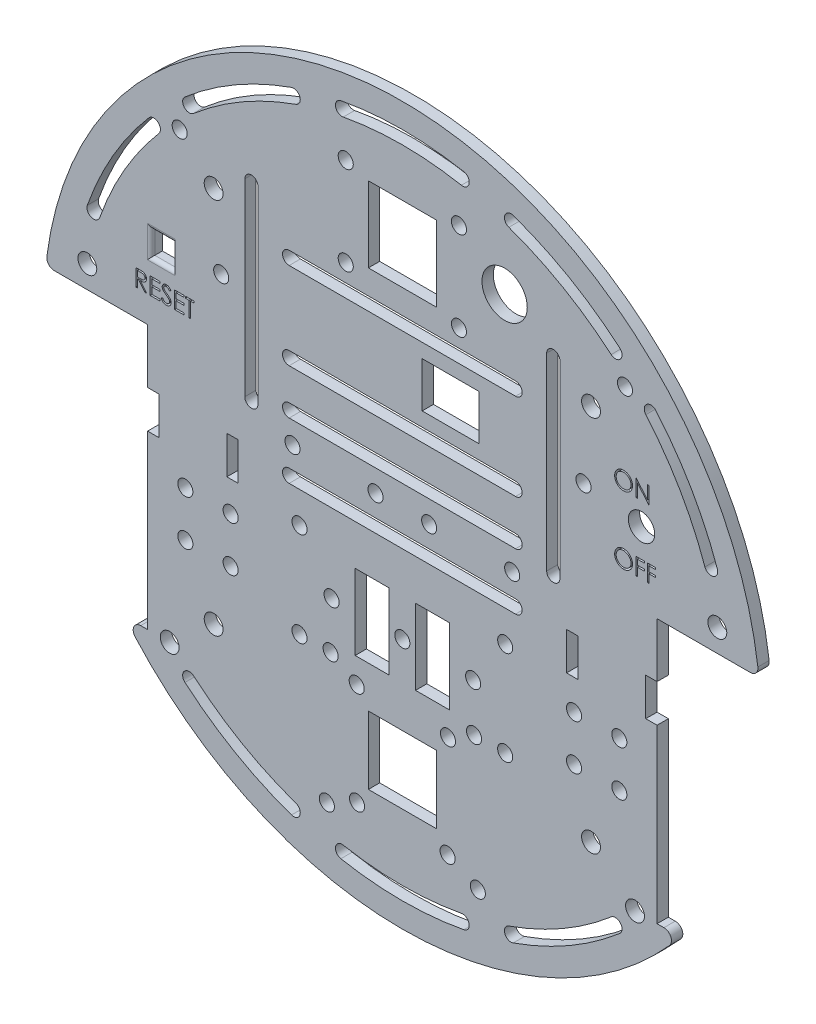
SolidWorks part; units mm, degrees
ref_plane "Alzado" through (0, 0, 0) normal (0, 0, 1) x (1, 0, 0)
ref_plane "Planta" through (0, 0, 0) normal (0, 1, 0) x (1, 0, 0)
ref_plane "Vista lateral" through (0, 0, 0) normal (1, 0, 0) x (0, 0, -1)
sketch "Croquis1" plane through (0, 0, 0) normal (0, 0, 1) x (1, 0, 0)
  line L0 (-73.6546, -60) -> (-67.5, -60)
  line L1 (-67.5, -60) -> (-67.5, -14.4456)
  line L2 (-67.5, 10) -> (-94.4722, 10)
  line L3 (0, 0) -> (0, 95) construction
  line L4 (67.5, 10) -> (94.4722, 10)
  line L5 (67.5, -60) -> (67.5, -14.4456)
  line L6 (73.6546, -60) -> (67.5, -60)
  line L7 (0, 0) -> (0, -95) construction
  line L8 (-66.5, -28.4456) -> (0, -28.4456) construction
  line L9 (12.5, -18.4456) -> (3.5, -18.4456)
  line L10 (-12.5, -38.4456) -> (-3.5, -38.4456)
  line L11 (-12.5, -38.4456) -> (-12.5, -18.4456)
  line L12 (-12.5, -18.4456) -> (-3.5, -18.4456)
  line L13 (-3.5, -38.4456) -> (-3.5, -18.4456)
  line L14 (-12.5, -38.4456) -> (-3.5, -18.4456) construction
  line L15 (-12.5, -18.4456) -> (-3.5, -38.4456) construction
  line L16 (3.5, -38.4456) -> (3.5, -18.4456)
  line L17 (12.5, -38.4456) -> (3.5, -38.4456)
  line L18 (12.5, -38.4456) -> (12.5, -18.4456)
  line L19 (-30, 9.0544) -> (30, 9.0544) construction
  line L22 (-30, 21.0544) -> (30, 21.0544) construction
  line L25 (0, 0) -> (-47.5, -82.2724) construction
  line L26 (-9, 52.25) -> (9, 52.25)
  line L27 (0, 0) -> (-82.2724, -47.5) construction
  line L28 (0, 0) -> (-95, 0) construction
  line L29 (0, 0) -> (-82.2724, 47.5) construction
  line L30 (0, 0) -> (-47.5, 82.2724) construction
  line L31 (0, 0) -> (0, 95) construction
  line L32 (0, 0) -> (47.5, 82.2724) construction
  line L33 (0, 0) -> (82.2724, 47.5) construction
  line L34 (0, 0) -> (95, 0) construction
  line L35 (0, 0) -> (82.2724, -47.5) construction
  line L36 (0, 0) -> (47.5, -82.2724) construction
  line L41 (-30, -5.9456) -> (30, -5.9456) construction
  line L42 (-30, -7.6956) -> (30, -7.6956)
  line L43 (-30, -4.1956) -> (30, -4.1956)
  line L44 (-9, -67.4313) -> (9, -67.4313)
  line L58 (-9, 52.25) -> (-9, 72.25)
  line L59 (-9, 72.25) -> (9, 72.25)
  line L61 (-40, 6.316) -> (-40, 56.316) construction
  line L62 (-41.75, 6.316) -> (-41.75, 56.316)
  line L63 (-38.25, 6.316) -> (-38.25, 56.316)
  line L64 (40, 6.316) -> (40, 56.316) construction
  line L65 (41.75, 6.316) -> (41.75, 56.316)
  line L66 (38.25, 6.316) -> (38.25, 56.316)
  line L67 (-30, 10.8044) -> (30, 10.8044)
  line L68 (-30, 7.3044) -> (30, 7.3044)
  line L71 (-30, 44.0544) -> (30, 44.0544) construction
  line L72 (-30, 45.8044) -> (30, 45.8044)
  line L73 (-30, 42.3044) -> (30, 42.3044)
  line L74 (-67.5, -4.4456) -> (-64.5, -4.4456)
  line L75 (-46.5, -4.4456) -> (-43.5, -4.4456)
  line L76 (-46.5, -4.4456) -> (-46.5, -14.4456)
  line L77 (-46.5, -14.4456) -> (-43.5, -14.4456)
  line L78 (-43.5, -4.4456) -> (-43.5, -14.4456)
  line L79 (-46.5, -4.4456) -> (-43.5, -14.4456) construction
  line L80 (-46.5, -14.4456) -> (-43.5, -4.4456) construction
  line L81 (-64.5, -4.4456) -> (-64.5, -14.4456)
  line L82 (-64.5, -14.4456) -> (-67.5, -14.4456)
  line L83 (46.5, -14.4456) -> (43.5, -4.4456) construction
  line L84 (46.5, -4.4456) -> (43.5, -14.4456) construction
  line L85 (46.5, -14.4456) -> (43.5, -14.4456)
  line L86 (43.5, -4.4456) -> (43.5, -14.4456)
  line L87 (46.5, -4.4456) -> (46.5, -14.4456)
  line L88 (46.5, -4.4456) -> (43.5, -4.4456)
  line L89 (64.5, -14.4456) -> (67.5, -14.4456)
  line L90 (64.5, -4.4456) -> (64.5, -14.4456)
  line L91 (67.5, -4.4456) -> (64.5, -4.4456)
  line L92 (-67.5, -4.4456) -> (-67.5, 10)
  line L93 (67.5, -4.4456) -> (67.5, 10)
  line L94 (-9, -67.4313) -> (-9, -49.4313)
  line L95 (-9, -49.4313) -> (9, -49.4313)
  line L96 (9, -67.4313) -> (9, -49.4313)
  line L97 (-9, -67.4313) -> (9, -49.4313) construction
  line L98 (-9, -49.4313) -> (9, -67.4313) construction
  line L99 (9, 52.25) -> (9, 72.25)
  line L100 (-9, 52.25) -> (9, 72.25) construction
  line L101 (-9, 72.25) -> (9, 52.25) construction
  line L102 (-30, 22.8044) -> (30, 22.8044)
  line L103 (-30, 19.3044) -> (30, 19.3044)
  line L105 (5.25, 26.5544) -> (20.25, 26.5544)
  line L106 (5.25, 26.5544) -> (5.25, 38.5544)
  line L107 (5.25, 38.5544) -> (20.25, 38.5544)
  line L108 (20.25, 26.5544) -> (20.25, 38.5544)
  line L109 (5.25, 26.5544) -> (20.25, 38.5544) construction
  line L110 (5.25, 38.5544) -> (20.25, 26.5544) construction
  line L111 (-66.5827, 25.8443) -> (-60.1827, 25.8443)
  line L112 (-66.5827, 25.8443) -> (-66.5827, 32.2443)
  line L113 (-66.5827, 32.2443) -> (-60.1827, 32.2443)
  line L114 (-60.1827, 25.8443) -> (-60.1827, 32.2443)
  line L115 (-66.5827, 25.8443) -> (-60.1827, 32.2443) construction
  line L116 (-66.5827, 32.2443) -> (-60.1827, 25.8443) construction
  arc A0 (-73.6546, -60) -> (73.6546, -60) centre (0, 0) ccw
  arc A1 (-16.2982, -86.9863) -> (16.2982, -86.9863) centre (0, 0) ccw
  arc A2 (-15.6507, -83.5467) -> (15.6507, -83.5467) centre (0, 0) ccw
  arc A3 (-15.6507, -83.5467) -> (-16.2982, -86.9863) centre (-15.973, -85.2668) ccw
  arc A4 (15.6507, -83.5467) -> (16.2982, -86.9863) centre (15.973, -85.2668) cw
  arc A5 (94.4722, 10) -> (-94.4722, 10) centre (0, 0) ccw
  circle A6 centre (-57.5, -22.4456) radius 2
  circle A7 centre (-45.5, -22.4456) radius 2
  circle A8 centre (-45.5, -34.4456) radius 2
  circle A9 centre (-57.5, -34.4456) radius 2
  circle A10 centre (-15, 50.5) radius 2
  circle A12 centre (-15, 74) radius 2
  circle A14 centre (45.5, -22.4456) radius 2
  circle A15 centre (45.5, -34.4456) radius 2
  circle A16 centre (57.5, -34.4456) radius 2
  circle A17 centre (57.5, -22.4456) radius 2
  circle A18 centre (0, -28.4456) radius 2
  circle A19 centre (15, 50.5) radius 2
  circle A20 centre (15, 74) radius 2
  arc A23 (-57.6078, -67.1833) -> (-29.3785, -83.4814) centre (0, 0) ccw
  arc A24 (-55.3273, -64.5282) -> (-28.2194, -80.1789) centre (0, 0) ccw
  arc A25 (-55.3273, -64.5282) -> (-57.6078, -67.1833) centre (-56.4664, -65.8567) ccw
  arc A26 (-28.2194, -80.1789) -> (-29.3785, -83.4814) centre (-28.8004, -81.8297) cw
  arc A35 (-67.1833, 57.6078) -> (-83.4814, 29.3785) centre (0, 0) ccw
  arc A36 (-64.5282, 55.3273) -> (-80.1789, 28.2194) centre (0, 0) ccw
  arc A37 (-64.5282, 55.3273) -> (-67.1833, 57.6078) centre (-65.8567, 56.4664) ccw
  arc A38 (-80.1789, 28.2194) -> (-83.4814, 29.3785) centre (-81.8297, 28.8004) cw
  arc A39 (-29.3785, 83.4814) -> (-57.6078, 67.1833) centre (0, 0) ccw
  arc A40 (-28.2194, 80.1789) -> (-55.3273, 64.5282) centre (0, 0) ccw
  arc A41 (-28.2194, 80.1789) -> (-29.3785, 83.4814) centre (-28.8004, 81.8297) ccw
  arc A42 (-55.3273, 64.5282) -> (-57.6078, 67.1833) centre (-56.4664, 65.8567) cw
  arc A47 (57.6078, 67.1833) -> (29.3785, 83.4814) centre (0, 0) ccw
  arc A48 (55.3273, 64.5282) -> (28.2194, 80.1789) centre (0, 0) ccw
  arc A49 (55.3273, 64.5282) -> (57.6078, 67.1833) centre (56.4664, 65.8567) ccw
  arc A50 (28.2194, 80.1789) -> (29.3785, 83.4814) centre (28.8004, 81.8297) cw
  arc A51 (83.4814, 29.3785) -> (67.1833, 57.6078) centre (0, 0) ccw
  arc A52 (80.1789, 28.2194) -> (64.5282, 55.3273) centre (0, 0) ccw
  arc A53 (80.1789, 28.2194) -> (83.4814, 29.3785) centre (81.8297, 28.8004) ccw
  arc A54 (64.5282, 55.3273) -> (67.1833, 57.6078) centre (65.8567, 56.4664) cw
  arc A63 (29.3785, -83.4814) -> (57.6078, -67.1833) centre (0, 0) ccw
  arc A64 (28.2194, -80.1789) -> (55.3273, -64.5282) centre (0, 0) ccw
  arc A65 (28.2194, -80.1789) -> (29.3785, -83.4814) centre (28.8004, -81.8297) ccw
  arc A66 (55.3273, -64.5282) -> (57.6078, -67.1833) centre (56.4664, -65.8567) cw
  arc A67 (64.5282, -55.3273) -> (80.1789, -28.2194) centre (0, 0) ccw [skipped]
  arc A68 (67.1833, -57.6078) -> (83.4814, -29.3785) centre (0, 0) ccw [skipped]
  arc A69 (80.1789, -28.2194) -> (83.4814, -29.3785) centre (81.8297, -28.8004) cw [skipped]
  arc A70 (64.5282, -55.3273) -> (67.1833, -57.6078) centre (65.8567, -56.4664) ccw [skipped]
  arc A71 (86.9863, -16.2982) -> (86.9863, 16.2982) centre (0, 0) ccw [skipped]
  arc A72 (83.5467, 15.6507) -> (86.9863, 16.2982) centre (85.2668, 15.973) cw [skipped]
  arc A73 (83.5467, -15.6507) -> (83.5467, 15.6507) centre (0, 0) ccw [skipped]
  arc A74 (83.5467, -15.6507) -> (86.9863, -16.2982) centre (85.2668, -15.973) ccw [skipped]
  arc A75 (-86.9863, 16.2982) -> (-86.9863, -16.2982) centre (0, 0) ccw [skipped]
  arc A76 (-83.5467, -15.6507) -> (-86.9863, -16.2982) centre (-85.2668, -15.973) cw [skipped]
  arc A77 (-83.5467, 15.6507) -> (-83.5467, -15.6507) centre (0, 0) ccw [skipped]
  arc A78 (-83.5467, 15.6507) -> (-86.9863, 16.2982) centre (-85.2668, 15.973) ccw [skipped]
  arc A79 (-83.4814, -29.3785) -> (-67.1833, -57.6078) centre (0, 0) ccw [skipped]
  arc A80 (-64.5282, -55.3273) -> (-67.1833, -57.6078) centre (-65.8567, -56.4664) cw [skipped]
  arc A81 (-80.1789, -28.2194) -> (-64.5282, -55.3273) centre (0, 0) ccw [skipped]
  arc A82 (-80.1789, -28.2194) -> (-83.4814, -29.3785) centre (-81.8297, -28.8004) ccw [skipped]
  arc A83 (16.2982, 86.9863) -> (-16.2982, 86.9863) centre (0, 0) ccw [skipped]
  arc A84 (-15.6507, 83.5467) -> (-16.2982, 86.9863) centre (-15.973, 85.2668) cw [skipped]
  arc A85 (15.6507, 83.5467) -> (-15.6507, 83.5467) centre (0, 0) ccw [skipped]
  arc A86 (15.6507, 83.5467) -> (16.2982, 86.9863) centre (15.973, 85.2668) ccw [skipped]
  circle A87 centre (-50, 50) radius 2.5
  arc A92 (-30, -7.6956) -> (-30, -4.1956) centre (-30, -5.9456) cw
  arc A93 (30, -4.1956) -> (30, -7.6956) centre (30, -5.9456) cw
  circle A94 centre (-27.25, -15.9456) radius 2
  circle A95 centre (-27.25, -40.9456) radius 2
  circle A96 centre (27.25, -40.9456) radius 2
  circle A97 centre (27.25, -15.9456) radius 2
  circle A98 centre (-50, -50) radius 2.5
  circle A99 centre (50, -50) radius 2.5
  circle A100 centre (50, 50) radius 2.5
  circle A113 centre (63.3827, 29.0443) radius 3.5
  circle A119 centre (-83.4722, 16) radius 2.5
  circle A120 centre (83.4722, 16) radius 2.5
  circle A121 centre (-61.6546, -60) radius 2.5
  circle A122 centre (61.6546, -60) radius 2.5
  arc A124 (-41.75, 6.316) -> (-38.25, 6.316) centre (-40, 6.316) ccw
  arc A125 (-38.25, 56.316) -> (-41.75, 56.316) centre (-40, 56.316) ccw
  arc A126 (41.75, 6.316) -> (38.25, 6.316) centre (40, 6.316) cw
  arc A127 (38.25, 56.316) -> (41.75, 56.316) centre (40, 56.316) cw
  circle A128 centre (-63.3827, 29.0443) radius 3.5 construction
  arc A129 (-30, 10.8044) -> (-30, 7.3044) centre (-30, 9.0544) ccw
  arc A130 (30, 7.3044) -> (30, 10.8044) centre (30, 9.0544) ccw
  arc A133 (-30, 45.8044) -> (-30, 42.3044) centre (-30, 44.0544) ccw
  arc A134 (30, 42.3044) -> (30, 45.8044) centre (30, 44.0544) ccw
  circle A135 centre (-48, 31.316) radius 2
  circle A136 centre (48, 31.316) radius 2
  arc A141 (-15.6507, 83.5467) -> (15.6507, 83.5467) centre (0, 0) cw
  arc A142 (-15.6507, 83.5467) -> (-16.2982, 86.9863) centre (-15.973, 85.2668) cw
  arc A143 (-16.2982, 86.9863) -> (16.2982, 86.9863) centre (0, 0) cw
  arc A144 (15.6507, 83.5467) -> (16.2982, 86.9863) centre (15.973, 85.2668) ccw
  circle A147 centre (-20, -75.9313) radius 2
  circle A148 centre (-19, -40.9456) radius 2
  circle A149 centre (19, -40.9456) radius 2
  circle A150 centre (20, -75.9313) radius 2
  circle A151 centre (-12, -71.9313) radius 2
  circle A152 centre (-12.0926, -44.9313) radius 2
  circle A153 centre (12, -71.9313) radius 2
  circle A154 centre (12.0926, -44.9313) radius 2
  circle A155 centre (18.75, -28.4456) radius 2
  circle A156 centre (-18.75, -28.4456) radius 2
  arc A157 (-30, 22.8044) -> (-30, 19.3044) centre (-30, 21.0544) ccw
  arc A158 (30, 19.3044) -> (30, 22.8044) centre (30, 21.0544) ccw
  circle A159 centre (-29.1055, 1.5544) radius 2
  circle A160 centre (-7.1056, 1.4826) radius 2
  circle A161 centre (7.1056, 1.4826) radius 2
  circle A162 centre (29.1055, 1.5544) radius 2
  circle A163 centre (27.1013, 64.25) radius 6
  circle A164 centre (-59, 59) radius 2
  circle A165 centre (59, 59) radius 2
  point P26 (-8, -28.4456)
  point P73 (0, -5.9456)
  point P136 (0, 0)
  point P161 (0, 9.0544)
  point P199 (0, 62.25)
  point P207 (0, 21.0544)
  point P230 (-40, 31.316)
  point P237 (40, 31.316)
  point P244 (-45, -9.4456)
  point P247 (0, 44.0544)
  point P275 (12.75, 32.5544)
  point P288 (0, -58.4313)
  dimension "D1" = 190
  dimension "D5" = 177
  dimension "D6" = 170
  dimension "D7" = 4
  dimension "D8" = 4
  dimension "D13" = 4
  dimension "D14" = 4
  dimension "D18" = 20
  dimension "D21" = 4
  dimension "4" = 4
  dimension "D24" = 50
  dimension "D25" = 5
  dimension "D30" = 4
  dimension "D32" = 20
  dimension "D38" = 60
  dimension "D40" = 15
  dimension "D42" = 7
  dimension "D46" = 20
  dimension "D47" = 5
  dimension "D50" = 5
  dimension "D52" = 11.75
  dimension "D53" = 4
  dimension "D64" = 12
  dimension "D65" = 3.5
  dimension "D68" = 4
  dimension "D26" = 4
  dimension "D69" = 4
  dimension "D72" = 4
  dimension "D67" = 4
  dimension "D76" = 4
  dimension "D84" = 12
  dimension "D83" = 4
  dimension "D85" = 59
  dimension "D2" = 70
  dimension "D3" = 135
  dimension "D4" = 35
  dimension "D9" = 6
  dimension "D10" = 6
  dimension "D11" = 12
  dimension "D12" = 10
  dimension "D15" = 23.5
  dimension "D16" = 15
  dimension "D17" = 21
  dimension "D19" = 9
  dimension "D20" = 55
  dimension "D22" = 12
  dimension "D23" = 50
  dimension "D27" = 19
  dimension "D28" = 35
  dimension "D29" = 12.5
  dimension "D31" = 18.25
  dimension "D33" = 12
  dimension "D34" = 37.5
  dimension "D35" = 60
  dimension "D36" = 3.5
  dimension "D37" = 60
  dimension "D39" = 23
  dimension "D41" = 3.5
  dimension "D43" = 18
  dimension "D44" = 3.5
  dimension "D45" = 40
  dimension "D48" = 6
  dimension "D49" = 11
  dimension "D51" = 12
  dimension "D54" = 18.75
  dimension "D55" = 50
  dimension "D56" = 3.5
  dimension "D57" = 3
  dimension "D58" = 10
  dimension "D59" = 19
  dimension "D60" = 3
  dimension "D61" = 10
  dimension "D62" = 18
  dimension "D63" = 48
  dimension "D66" = 7.5
  dimension "D70" = 27
  dimension "D71" = 4
  dimension "D73" = 13.5
  dimension "D74" = 18
  dimension "D75" = 18
  dimension "D77" = 22
  dimension "D78" = 15
  dimension "D79" = 12
  dimension "D80" = 11.5
  dimension "D81" = 6.4
  dimension "D82" = 6.4
  dimension "D86" = 59
extrude "Saliente-Extruir1" add sketch "Croquis1" along normal blind 3
fillet "Redondeo2" radius 2 4 edges at (-94.4722, 10, 1.5) (-73.6546, -60, 1.5) (73.6546, -60, 1.5) (94.4722, 10, 1.5)
sketch "Croquis2" plane through (0, 0, 3) normal (0, 0, 1) x (1, 0, 0)
  line L2 (55.9162, 35.0065) -> (66.1121, 35.0065) construction
  line L3 (-71.1868, 17.0238) -> (-45.4634, 17.0238) construction
  line L4 (55.9162, 17.0238) -> (72.9529, 17.0238) construction
  line L6 (-66.1702, 35.0065) -> (-56.7811, 35.0065) construction
  text T1 "ON" font "Century Gothic" height 4.5
  text T2 "RESET" font "Century Gothic" height 4.5
  text T3 "OFF" font "Century Gothic" height 4.5
extrude "Cortar-Extruir2" cut sketch "Croquis2" against normal blind 2
fillet "Redondeo3" radius 1 3 edges at (-63.3827, 32.2443, 3) (-63.3827, 25.8443, 3) (-66.5827, 29.0443, 3)
